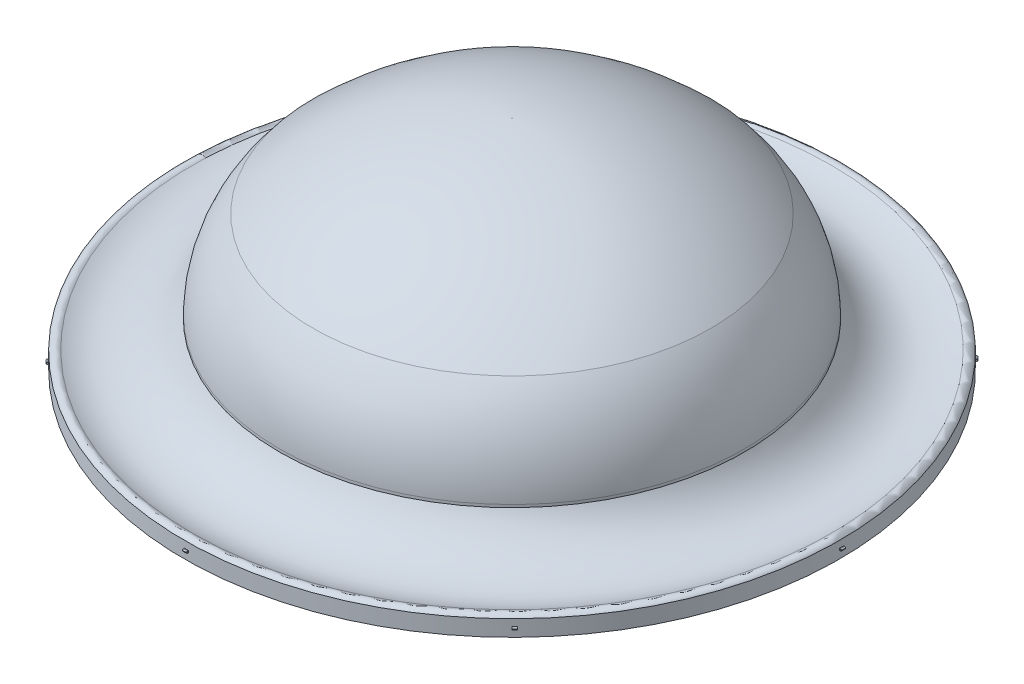
SolidWorks part; units mm, degrees
ref_plane "Alzado" through (0, 0, 0) normal (0, 0, 1) x (1, 0, 0)
ref_plane "Planta" through (0, 0, 0) normal (0, 1, 0) x (1, 0, 0)
ref_plane "Vista lateral" through (0, 0, 0) normal (1, 0, 0) x (0, 0, -1)
sketch "Croquis1" plane through (0, 0, 0) normal (1, 0, 0) x (0, 0, -1)
  line L0 (-53.7067, -38.0021) -> (-53.7067, -39.8629)
  line L1 (-58.7067, -37.949) -> (-58.7067, -38.6406)
  line L2 (0, 0) -> (0, 4.9986)
  line L3 (0, 4.9986) -> (-0.1196, 4.9986)
  line L4 (-0.1196, 4.9986) -> (-0.1185, 4.991)
  line L5 (-82.75, -50) -> (-82.75, -45.9136)
  arc A0 (0, 0) -> (-46.5906, -19.2753) centre (1.6753, -69.9944) ccw
  arc A1 (-46.5906, -19.2753) -> (-53.7067, -38.0021) centre (-23.7684, -38.6632) ccw
  arc A2 (-0.1196, 4.9986) -> (-50.2251, -15.8325) centre (1.6753, -69.9944) ccw
  arc A3 (-53.7067, -39.8629) -> (-82.75, -50) centre (-73.2969, -30.4098) cw
  arc A4 (-50.2251, -15.8325) -> (-58.7067, -37.949) centre (-23.7684, -38.6632) ccw
  arc A5 (-58.7067, -38.6406) -> (-80.5771, -45.4969) centre (-73.2969, -30.4098) cw
  arc A6 (-82.75, -45.9136) -> (-80.5771, -45.4969) centre (-81.4551, -46.7917) cw
  dimension "D1" = 5
revolve "Revolución1" add sketch "Croquis1" angle 360 about L2
sketch "Croquis3" plane through (0, 0, 0) normal (0, 0, 1) x (1, 0, 0)
  line L1 (-82.6698, -47.6192) -> (-82.9612, -47.6192)
  line L2 (-82.6698, -47.6192) -> (-82.6698, -48.1536)
  line L3 (-82.6698, -48.1536) -> (-82.9612, -48.1536)
  line L4 (-83.2112, -47.8692) -> (-83.2112, -47.9036)
  circle A0 centre (-82.953, -47.8765) radius 0.15
  arc A1 (-82.9612, -48.1536) -> (-83.2112, -47.9036) centre (-82.9612, -47.9036) cw
  arc A2 (-82.9612, -47.6192) -> (-83.2112, -47.8692) centre (-82.9612, -47.8692) ccw
  dimension "D1" = 0.3
  dimension "D2" = 0.25
extrude "Saliente-Extruir1" add sketch "Croquis3" along normal blind 1
pattern_circular "MatrizC1" count 8 every 45 about axis through (0, 0, 0) along (0, 1, 0) of "Saliente-Extruir1"
sketch "Croquis4" plane through (0, 0, 0) normal (1, 0, 0) x (0, 0, -1)
  line L0 (-13.4634, -1.8739) -> (14.5275, -1.8739)
  arc A0 (-13.4634, -1.8739) -> (14.5275, -1.8739) centre (0.5321, -42.8001) cw
extrude "Cortar-Extruir1" cut sketch "Croquis4" against normal blind 3.5 and the other way blind 3.5
